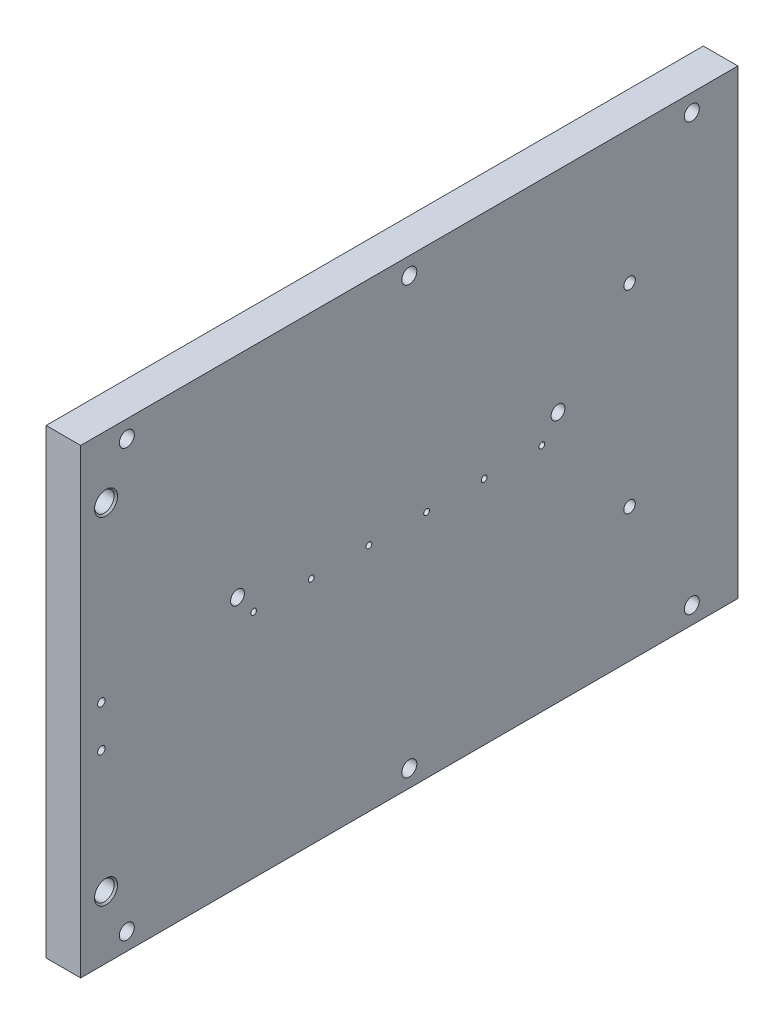
SolidWorks part; units mm, degrees
ref_plane "Front" through (0, 0, 0) normal (0, 0, 1) x (1, 0, 0)
ref_plane "Top" through (0, 0, 0) normal (0, 1, 0) x (1, 0, 0)
ref_plane "Right" through (0, 0, 0) normal (1, 0, 0) x (0, 0, -1)
sketch "Sketch1" plane through (0, 0, 0) normal (1, 0, 0) x (0, 0, -1)
  line L1 (0, 0) -> (-285, 0)
  line L2 (0, 0) -> (0, 200)
  line L3 (0, 200) -> (-285, 200)
  line L4 (-285, 0) -> (-285, 200)
  dimension "D1" = 200
  dimension "D2" = 285
extrude "Boss-Extrude1" add sketch "Sketch1" against normal blind 15
sketch "Sketch4" plane through (0, 0, 0) normal (1, 0, 0) x (0, 0, -1)
  line L0 (0, 0) -> (0, 200) construction
  line L1 (-285, 0) -> (0, 0) construction
  circle A0 centre (-217, 109) radius 3
  circle A1 centre (-78, 109) radius 3
  dimension "D1" = 6
  dimension "D2" = 78
  dimension "D3" = 139
  dimension "D4" = 109
extrude "Cut-Extrude1" cut sketch "Sketch4" against normal blind 7
hole_wizard "M6 Tapped Hole1" positions "Sketch3" profile "Sketch2" tap size "M6" standard "ISO"
sketch "Sketch3" plane through (0, 0, 0) normal (0, 0, -1) x (-1, 0, 0)
  line L0 (0, 0) -> (0, 200) construction
  line L1 (15, 0) -> (0, 0) construction
  point P0 (7.5, 25)
  point P1 (7.5, 100)
  point P3 (7.5, 175)
  dimension "D1" = 7.5
  dimension "D2" = 25
  dimension "D3" = 75
  dimension "D4" = 75
sketch "Sketch2" plane through (-7.5, 25, 0) normal (1, 0, 0) x (0, 1, 0)
  line L0 (0, 0) -> (0, 11.5022)
  line L1 (0, 11.5022) -> (2.5, 10)
  line L2 (2.5, 10) -> (2.5, 0)
  line L5 (2.5, 0) -> (0, 0)
  line L10 (0, 11.5022) -> (-2.5, 10) construction
  line L11 (0, -6.35) -> (0, 107.95) construction
  dimension "Tap Drill Dia." = 5
  dimension "Tap Drill Depth" = 10
  dimension "Drill Angle" = 118
cosmetic thread "Hole Thread1" parameters "D1"=7, "D2"=6
cosmetic thread "Hole Thread2" parameters "D1"=7, "D2"=6
cosmetic thread "Hole Thread3" parameters "D1"=7, "D2"=6
hole_wizard "M3 Tapped Hole1" positions "Sketch6" profile "Sketch5" tap size "M3" standard "ISO"
sketch "Sketch6" plane through (0, 0, 0) normal (1, 0, 0) x (0, 0, -1)
  line L0 (-285, 0) -> (0, 0) construction
  line L1 (0, 0) -> (0, 200) construction
  point P0 (-85, 100)
  dimension "D1" = 100
  dimension "D2" = 85
sketch "Sketch5" plane through (0, 100, 85) normal (0, 1, 0) x (0, 0, -1)
  line L0 (0, 0) -> (0, 8.2511)
  line L1 (0, 8.2511) -> (1.25, 7.5)
  line L2 (1.25, 7.5) -> (1.25, 0)
  line L5 (1.25, 0) -> (0, 0)
  line L10 (0, 8.2511) -> (-1.25, 7.5) construction
  line L11 (0, -6.35) -> (0, 107.95) construction
  dimension "Tap Drill Dia." = 2.5
  dimension "Tap Drill Depth" = 7.5
  dimension "Drill Angle" = 118
cosmetic thread "Hole Thread4" parameters "D1"=6, "D2"=3
pattern_linear "LPattern1" count 6 spacing 25 along (0, 0, 1) of "M3 Tapped Hole1"
hole_wizard "M6 Tapped Hole2" positions "Sketch8" profile "Sketch7" tap size "M6" standard "ISO"
sketch "Sketch8" plane through (0, 0, 0) normal (1, 0, 0) x (0, 0, -1)
  line L0 (0, 0) -> (0, 200) construction
  line L1 (-285, 0) -> (0, 0) construction
  point P0 (-47, 58)
  point P1 (-47, 142)
  dimension "D1" = 47
  dimension "D2" = 58
  dimension "D3" = 84
sketch "Sketch7" plane through (0, 58, 47) normal (0, 1, 0) x (0, 0, -1)
  line L0 (0, 0) -> (0, 11.5022)
  line L1 (0, 11.5022) -> (2.5, 10)
  line L2 (2.5, 10) -> (2.5, 0)
  line L5 (2.5, 0) -> (0, 0)
  line L10 (0, 11.5022) -> (-2.5, 10) construction
  line L11 (0, -6.35) -> (0, 107.95) construction
  dimension "Tap Drill Dia." = 5
  dimension "Tap Drill Depth" = 10
  dimension "Drill Angle" = 118
cosmetic thread "Hole Thread5" parameters "D1"=7, "D2"=6
cosmetic thread "Hole Thread6" parameters "D1"=7, "D2"=6
hole_wizard "M4 Tapped Hole1" positions "Sketch10" profile "Sketch9" tap size "M4" standard "ISO"
sketch "Sketch10" plane through (0, 0, 0) normal (1, 0, 0) x (0, 0, -1)
  line L0 (-285, 0) -> (0, 0) construction
  line L1 (0, 0) -> (0, 200) construction
  point P0 (-276, 81)
  point P1 (-276, 99)
  dimension "D1" = 81
  dimension "D2" = 18
  dimension "D3" = 276
sketch "Sketch9" plane through (0, 81, 276) normal (0, 1, 0) x (0, 0, -1)
  line L0 (0, 0) -> (0, 11.0914)
  line L1 (0, 11.0914) -> (1.65, 10.1)
  line L2 (1.65, 10.1) -> (1.65, 0)
  line L5 (1.65, 0) -> (0, 0)
  line L10 (0, 11.0914) -> (-1.65, 10.1) construction
  line L11 (0, -6.35) -> (0, 107.95) construction
  dimension "Tap Drill Dia." = 3.3
  dimension "Tap Drill Depth" = 10.1
  dimension "Drill Angle" = 118
cosmetic thread "Hole Thread7" parameters "D1"=8, "D2"=4
cosmetic thread "Hole Thread8" parameters "D1"=8, "D2"=4
hole_wizard "M10 Tapped Hole1" positions "Sketch12" profile "Sketch11" tap size "M10" standard "ISO" end condition through all
sketch "Sketch12" plane through (0, 0, 0) normal (1, 0, 0) x (0, 0, -1)
  line L0 (-285, 0) -> (0, 0) construction
  line L1 (0, 0) -> (0, 200) construction
  point P0 (-274, 27)
  point P1 (-274, 173)
  dimension "D1" = 27
  dimension "D2" = 146
  dimension "D3" = 274
cosmetic thread "Hole Thread9" parameters "D2"=10
cosmetic thread "Hole Thread10" parameters "D2"=10
sketch "Sketch11" plane through (0, 27, 274) normal (0, 1, 0) x (0, 0, -1)
  line L0 (0, 0) -> (0, 15)
  line L1 (0, 15) -> (4.25, 15)
  line L2 (4.25, 15) -> (4.25, 0.75)
  line L3 (4.25, 0.75) -> (5, 0)
  line L5 (5, 0) -> (0, 0)
  line L6 (-4.25, 0.75) -> (-5, 0) construction
  line L11 (0, -6.35) -> (0, 107.95) construction
  dimension "Thru Tap Drill Dia." = 8.5
  dimension "Thru Tap Drill Depth" = 15
  dimension "Near C'Sink Dia." = 10
  dimension "Near C'Sink Angle" = 90
hole_wizard "Ø6.5 (6.5) Diameter Hole1" positions "Sketch14" profile "Sketch13" hole size "Ø6.5" standard "ISO" end condition through all
sketch "Sketch14" plane through (0, 0, 0) normal (1, 0, 0) x (0, 0, -1)
  line L0 (-285, 0) -> (0, 0) construction
  line L1 (0, 0) -> (0, 200) construction
  point P0 (-265, 7.5)
  point P1 (-142.5, 7.5)
  point P3 (-20, 7.5)
  point P5 (-20, 192.5)
  point P7 (-142.5, 192.5)
  point P9 (-265, 192.5)
  dimension "D1" = 7.5
  dimension "D2" = 185
  dimension "D3" = 20
  dimension "D4" = 122.5
  dimension "D5" = 122.5
sketch "Sketch13" plane through (0, 7.5, 265) normal (0, 1, 0) x (0, 0, -1)
  line L0 (0, 0) -> (0, 15)
  line L1 (0, 15) -> (3.25, 15)
  line L2 (3.25, 15) -> (3.25, 0)
  line L5 (3.25, 0) -> (0, 0)
  line L11 (0, -6.35) -> (0, 107.95) construction
  dimension "Thru Hole Dia." = 6.5
  dimension "Thru Hole Depth" = 15
